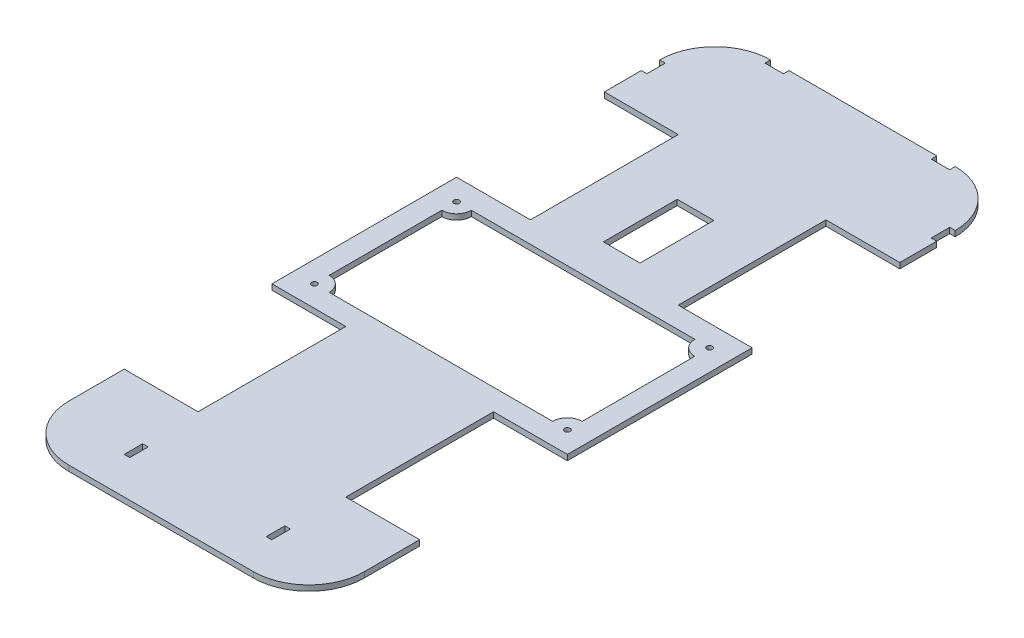
SolidWorks part; units mm, degrees
ref_plane "Plano frontal" through (0, 0, 0) normal (0, 0, 1) x (1, 0, 0)
ref_plane "Plano superior" through (0, 0, 0) normal (0, 1, 0) x (1, 0, 0)
ref_plane "Plano direito" through (0, 0, 0) normal (1, 0, 0) x (0, 0, -1)
sketch "Esboço1" plane through (0, 0, 0) normal (0, 1, 0) x (1, 0, 0)
  line L0 (-25.8241, -23.3002) -> (74.1759, -23.3002)
  line L1 (-55.8241, 6.6998) -> (-55.8241, 36.6998)
  line L2 (-55.8241, 36.6998) -> (-15.8241, 36.6998)
  line L3 (-15.8241, 36.6998) -> (-15.8241, 116.6998)
  line L4 (-15.8241, 116.6998) -> (-55.8241, 116.6998)
  line L5 (-55.8241, 116.6998) -> (-55.8241, 216.6998)
  line L6 (104.1759, 6.6998) -> (104.1759, 36.6998)
  line L7 (104.1759, 36.6998) -> (64.1759, 36.6998)
  line L8 (64.1759, 36.6998) -> (64.1759, 116.6998)
  line L9 (64.1759, 116.6998) -> (104.1759, 116.6998)
  line L10 (104.1759, 116.6998) -> (104.1759, 216.6998)
  line L11 (-55.8241, 216.6998) -> (-15.8241, 216.6998)
  line L12 (-15.8241, 216.6998) -> (-15.8241, 296.6998)
  line L13 (-15.8241, 296.6998) -> (-55.8241, 296.6998)
  line L14 (-55.8241, 296.6998) -> (-55.8241, 326.6998)
  line L15 (104.1759, 216.6998) -> (64.1759, 216.6998)
  line L16 (64.1759, 216.6998) -> (64.1759, 296.6998)
  line L17 (64.1759, 296.6998) -> (104.1759, 296.6998)
  line L18 (104.1759, 296.6998) -> (104.1759, 326.6998)
  line L27 (-25.8241, 356.6998) -> (74.1759, 356.6998)
  arc A0 (-55.8241, 326.6998) -> (-25.8241, 356.6998) centre (-25.8241, 326.6998) cw
  arc A2 (74.1759, 356.6998) -> (104.1759, 326.6998) centre (74.1759, 326.6998) cw
  arc A4 (-55.8241, 6.6998) -> (-25.8241, -23.3002) centre (-25.8241, 6.6998) ccw
  arc A5 (104.1759, 6.6998) -> (74.1759, -23.3002) centre (74.1759, 6.6998) cw
extrude "Ressalto-extrusão1" add sketch "Esboço1" along normal blind 3
sketch "Esboço2" plane through (0, 3, 0) normal (0, 1, 0) x (1, 0, 0)
  line L0 (104.1759, 116.6998) -> (104.1759, 216.6998) construction
  line L1 (104.1759, 326.6998) -> (101.1759, 326.6998)
  line L2 (101.1759, 326.6998) -> (101.1759, 316.6998)
  line L3 (101.1759, 316.6998) -> (104.1759, 316.6998)
  line L4 (104.1759, 296.6998) -> (104.1759, 326.6998) construction
  line L5 (104.1759, 316.6998) -> (104.1759, 326.6998)
  line L6 (74.1759, 356.6998) -> (74.1759, 353.6998)
  line L7 (74.1759, 353.6998) -> (64.1759, 353.6998)
  line L8 (64.1759, 116.6998) -> (104.1759, 116.6998) construction
  line L9 (64.1759, 353.6998) -> (64.1759, 356.6998)
  line L10 (104.1759, 216.6998) -> (64.1759, 216.6998) construction
  line L11 (-15.8241, 216.6998) -> (-55.8241, 216.6998) construction
  line L12 (-55.8241, 216.6998) -> (-55.8241, 116.6998) construction
  line L13 (-55.8241, 116.6998) -> (-15.8241, 116.6998) construction
  line L14 (-36.3241, 205.1998) -> (84.6759, 205.1998)
  line L15 (-44.3241, 197.1998) -> (-44.3241, 136.1998)
  line L16 (-36.3241, 128.1998) -> (84.6759, 128.1998)
  line L17 (92.6759, 136.1998) -> (92.6759, 197.1998)
  line L18 (-55.8241, 36.6998) -> (-55.8241, 6.6998) construction
  line L19 (-15.8241, 6.6998) -> (-12.8241, 6.6998)
  line L20 (-15.8241, 6.6998) -> (-15.8241, -3.3002)
  line L21 (-15.8241, -3.3002) -> (-12.8241, -3.3002)
  line L22 (-12.8241, 6.6998) -> (-12.8241, -3.3002)
  line L23 (-15.8241, 36.6998) -> (-55.8241, 36.6998) construction
  line L24 (104.1759, 36.6998) -> (64.1759, 36.6998) construction
  line L25 (61.1759, 6.6998) -> (64.1759, 6.6998)
  line L26 (61.1759, 6.6998) -> (61.1759, -3.4029)
  line L27 (61.1759, -3.4029) -> (64.1759, -3.4029)
  line L28 (64.1759, 6.6998) -> (64.1759, -3.4029)
  line L29 (104.1759, 6.6998) -> (104.1759, 36.6998) construction
  line L30 (74.1759, 356.6998) -> (-25.8241, 356.6998) construction
  line L31 (64.1759, 356.6998) -> (74.1759, 356.6998)
  line L32 (-25.8241, 356.6998) -> (-25.8241, 353.6998)
  line L33 (-25.8241, 353.6998) -> (-15.8241, 353.6998)
  line L34 (-15.8241, 353.6998) -> (-15.8241, 356.6998)
  line L35 (-15.8241, 356.6998) -> (-25.8241, 356.6998)
  line L36 (-55.8241, 326.6998) -> (-52.8241, 326.6998)
  line L37 (-52.8241, 326.6998) -> (-52.8241, 316.6998)
  line L38 (-52.8241, 316.6998) -> (-55.8241, 316.6998)
  line L39 (-55.8241, 326.6998) -> (-55.8241, 296.6998) construction
  line L40 (-55.8241, 316.6998) -> (-55.8241, 326.6998)
  line L50 (-15.8241, 296.6998) -> (-15.8241, 216.6998) construction
  line L51 (64.1759, 216.6998) -> (64.1759, 296.6998) construction
  line L52 (64.1759, 296.6998) -> (104.1759, 296.6998) construction
  line L53 (34.1009, 256.6998) -> (34.1009, 266.0998)
  line L54 (14.2509, 256.6998) -> (14.2509, 266.0998)
  line L55 (14.2509, 266.0998) -> (34.1009, 266.0998)
  line L56 (14.2509, 256.6998) -> (14.2509, 226.0998)
  line L57 (14.2509, 226.0998) -> (34.1009, 226.0998)
  line L58 (34.1009, 226.0998) -> (34.1009, 256.6998)
  circle A0 centre (-44.3241, 205.1998) radius 1.5
  circle A1 centre (-44.3241, 128.1998) radius 1.5
  circle A2 centre (92.6759, 128.1998) radius 1.5
  circle A3 centre (92.6759, 205.1998) radius 1.5
  arc A4 (84.6759, 128.1998) -> (92.6759, 136.1998) centre (92.6759, 128.1998) cw
  arc A5 (92.6759, 197.1998) -> (84.6759, 205.1998) centre (92.6759, 205.1998) cw
  arc A6 (-44.3241, 197.1998) -> (-36.3241, 205.1998) centre (-44.3241, 205.1998) ccw
  arc A7 (-36.3241, 128.1998) -> (-44.3241, 136.1998) centre (-44.3241, 128.1998) ccw
  dimension "D1" = 11.5
  dimension "D2" = 11.5
  dimension "D3" = 11.5
  dimension "D4" = 11.5
  dimension "D5" = 11.5
  dimension "D6" = 11.5
  dimension "D7" = 11.5
  dimension "D8" = 11.5
  dimension "D11" = 8
  dimension "D13" = 8
  dimension "D15" = 8
  dimension "D16" = 8
  dimension "D27" = 30.075
  dimension "D9" = 8
  dimension "D10" = 8
  dimension "D12" = 8
  dimension "D14" = 8
  dimension "D17" = 40
  dimension "D18" = 30
  dimension "D19" = 30
  dimension "D20" = 40
  dimension "D21" = 3
  dimension "D22" = 10
  dimension "D24" = 80
  dimension "D25" = 80
  dimension "D26" = 30.075
  dimension "D29" = 30.6
extrude "Corte-extrusão2" cut sketch "Esboço2" against normal blind 3
